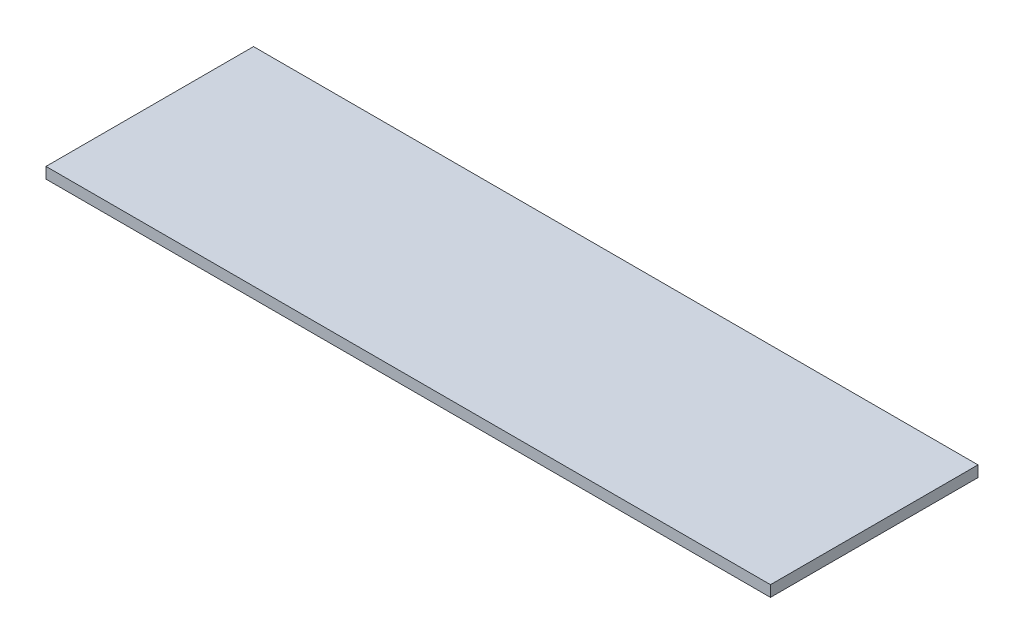
SolidWorks part; units mm, degrees
ref_plane "Front Plane" through (0, 0, 0) normal (0, 0, 1) x (1, 0, 0)
ref_plane "Top Plane" through (0, 0, 0) normal (0, 1, 0) x (1, 0, 0)
ref_plane "Right Plane" through (0, 0, 0) normal (1, 0, 0) x (0, 0, -1)
sketch "Sketch1" plane through (0, 0, 0) normal (0, 1, 0) x (1, 0, 0)
  line L1 (147.5, -42.25) -> (-147.5, -42.25)
  line L2 (147.5, -42.25) -> (147.5, 42.25)
  line L3 (147.5, 42.25) -> (-147.5, 42.25)
  line L4 (-147.5, -42.25) -> (-147.5, 42.25)
  line L5 (147.5, -42.25) -> (-147.5, 42.25) construction
  line L6 (147.5, 42.25) -> (-147.5, -42.25) construction
  point P0 (0, 0)
  dimension "D1" = 295
  dimension "D2" = 84.5
extrude "Boss-Extrude1" add sketch "Sketch1" along normal blind 4.5
